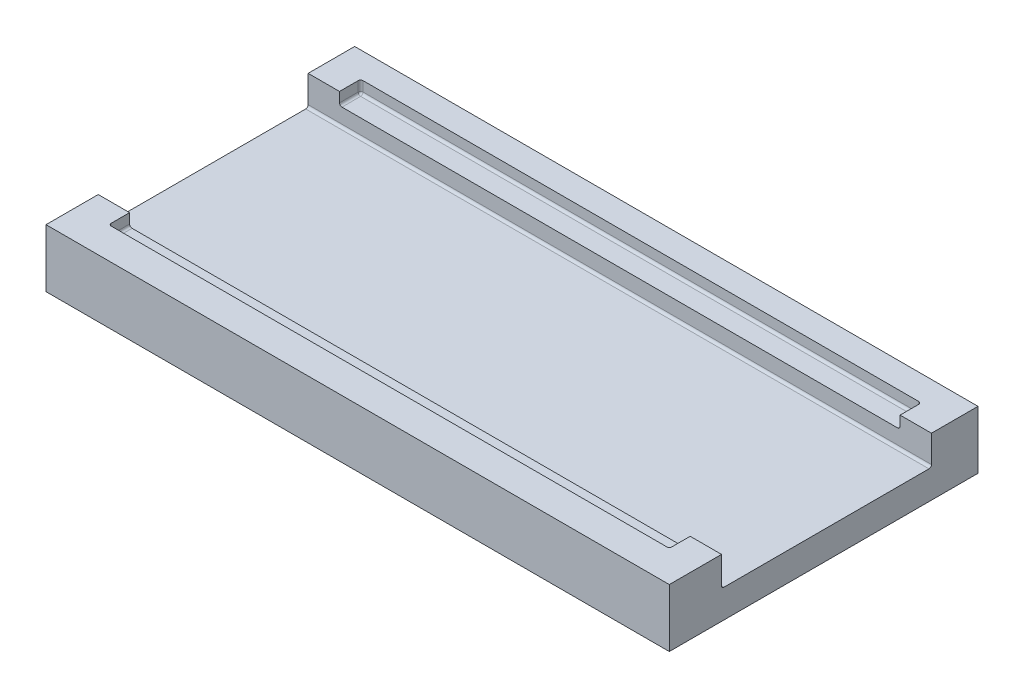
SolidWorks part; units mm, degrees
ref_plane "Front Plane" through (0, 0, 0) normal (0, 0, 1) x (1, 0, 0)
ref_plane "Top Plane" through (0, 0, 0) normal (0, 1, 0) x (1, 0, 0)
ref_plane "Right Plane" through (0, 0, 0) normal (1, 0, 0) x (0, 0, -1)
sketch "Sketch1" plane through (0, 0, 0) normal (0, 1, 0) x (1, 0, 0)
  line L1 (0, 0) -> (252.4, 0)
  line L2 (0, 0) -> (0, 125)
  line L3 (0, 125) -> (252.4, 125)
  line L4 (252.4, 0) -> (252.4, 125)
  dimension "D1" = 125
  dimension "D2" = 252.4
extrude "Boss-Extrude1" add sketch "Sketch1" along normal blind 23.5
sketch "Sketch2" plane through (0, 23.5, 0) normal (0, 1, 0) x (1, 0, 0)
  line L0 (0, 125) -> (0, 0) construction
  line L1 (12.7, 114.7) -> (239.7, 114.7)
  line L2 (12.7, 114.7) -> (12.7, 12.7)
  line L3 (12.7, 12.7) -> (239.7, 12.7)
  line L4 (239.7, 114.7) -> (239.7, 12.7)
  line L5 (0, 0) -> (252.4, 0) construction
  dimension "D1" = 12.7
  dimension "D2" = 12.7
  dimension "D3" = 102
  dimension "D4" = 227
extrude "Cut-Extrude1" cut sketch "Sketch2" against normal blind 5
sketch "Sketch3" plane through (0, 18.5, 0) normal (0, 1, 0) x (1, 0, 0)
  line L0 (239.7, 12.7) -> (239.7, 114.7) construction
  line L1 (239.7, 106.15) -> (12.7, 106.15)
  line L2 (239.7, 106.15) -> (239.7, 21.15)
  line L3 (239.7, 21.15) -> (12.7, 21.15)
  line L4 (12.7, 106.15) -> (12.7, 21.15)
  line L8 (239.7, 114.7) -> (12.7, 114.7) construction
  dimension "D1" = 227
  dimension "D2" = 85
  dimension "D3" = 8.55
extrude "Cut-Extrude2" cut sketch "Sketch3" against normal blind 7
sketch "Sketch4" plane through (0, 23.5, 0) normal (0, 1, 0) x (1, 0, 0)
  line L0 (0, 125) -> (0, 0) construction
  line L1 (0, 21.15) -> (12.7, 21.15)
  line L2 (0, 21.15) -> (0, 106.15)
  line L3 (0, 106.15) -> (12.7, 106.15)
  line L4 (12.7, 21.15) -> (12.7, 106.15)
  line L5 (12.7, 114.7) -> (12.7, 12.7) construction
  line L8 (12.7, 21.15) -> (239.7, 21.15) construction
  dimension "D1" = 85
extrude "Cut-Extrude3" cut sketch "Sketch4" against normal blind 12
sketch "Sketch5" plane through (0, 23.5, 0) normal (0, 1, 0) x (1, 0, 0)
  line L0 (239.7, 12.7) -> (239.7, 114.7) construction
  line L1 (239.7, 21.15) -> (252.4, 21.15)
  line L2 (239.7, 21.15) -> (239.7, 106.15)
  line L3 (239.7, 106.15) -> (252.4, 106.15)
  line L4 (252.4, 21.15) -> (252.4, 106.15)
  line L5 (252.4, 0) -> (252.4, 125) construction
  line L6 (0, 21.15) -> (239.7, 21.15) construction
  dimension "D1" = 85
extrude "Cut-Extrude4" cut sketch "Sketch5" against normal up to surface (12 mm away) up to face at (119.85, 11.5, -63.65)
fillet "Fillet1" radius 1 12 edges at (239.7, 21, -12.7) (239.7, 18.5, -16.925) (12.7, 18.5, -16.925) (12.7, 21, -12.7) (126.2, 18.5, -12.7) (126.2, 11.5, -21.15) (12.7, 21, -114.7) (239.7, 21, -114.7) (239.7, 18.5, -110.425) (12.7, 18.5, -110.425) (126.2, 11.5, -106.15) (126.2, 18.5, -114.7)
